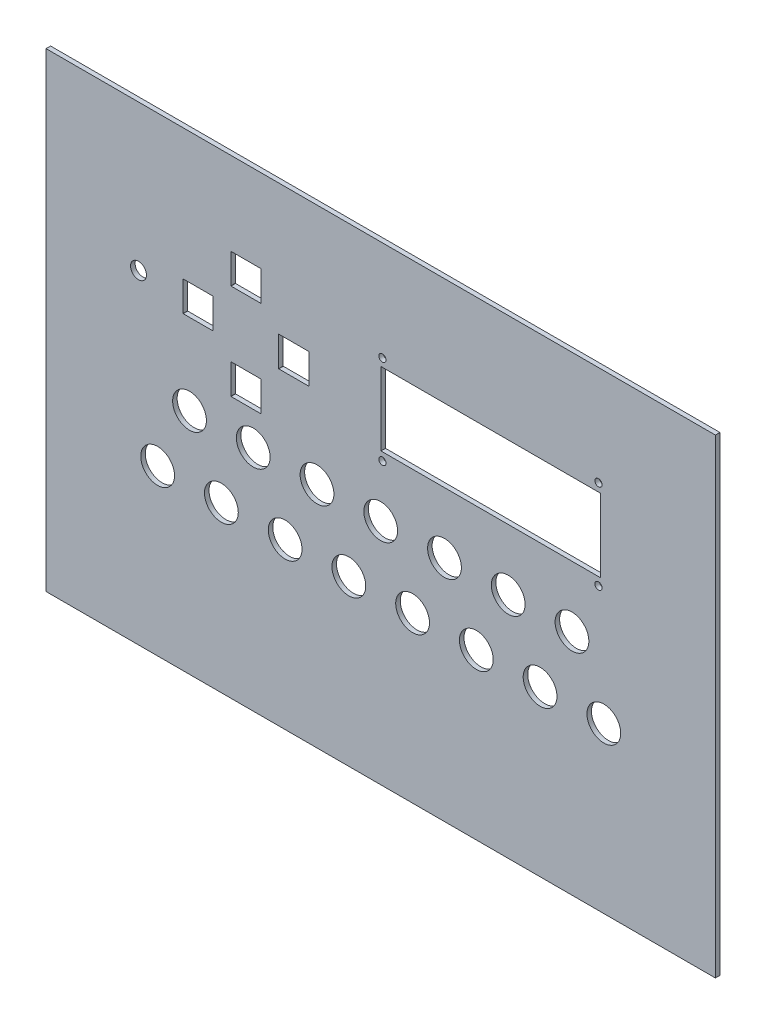
SolidWorks part; units mm, degrees
ref_plane "Front Plane" through (0, 0, 0) normal (0, 0, 1) x (1, 0, 0)
ref_plane "Top Plane" through (0, 0, 0) normal (0, 1, 0) x (1, 0, 0)
ref_plane "Right Plane" through (0, 0, 0) normal (1, 0, 0) x (0, 0, -1)
sketch "Model" plane through (0, 0, 0) normal (0, 0, 1) x (1, 0, 0)
  line L21 (196.2082, 34.8915) -> (-36.2018, 34.8915)
  line L22 (196.2082, 34.8915) -> (196.2082, 198.1627)
  line L23 (196.2082, 198.1627) -> (-36.2018, 198.1627)
  line L24 (-36.2018, 34.8915) -> (-36.2018, 198.1627)
  point P16 (80.0032, 34.8915)
  line B0 (28.0165, 169.3095) -> (38.375, 169.3095)
  line B1 (38.4192, 169.2652) -> (38.4192, 158.9068)
  line B2 (38.375, 158.8625) -> (28.0165, 158.8625)
  line B3 (27.9722, 158.9068) -> (27.9722, 169.2652)
  line B4 (28.0165, 136.1093) -> (38.375, 136.1093)
  line B5 (38.4192, 136.065) -> (38.4192, 125.7065)
  line B6 (38.375, 125.6623) -> (28.0165, 125.6623)
  line B7 (27.9722, 125.7065) -> (27.9722, 136.065)
  line B8 (44.6166, 152.7094) -> (54.9751, 152.7094)
  line B9 (55.0194, 152.6651) -> (55.0194, 142.3066)
  line B10 (54.9751, 142.2624) -> (44.6166, 142.2624)
  line B11 (44.5724, 142.3066) -> (44.5724, 152.6651)
  line B12 (21.8191, 152.6651) -> (21.8191, 142.3066)
  line B13 (21.7749, 142.2624) -> (11.4164, 142.2624)
  line B14 (11.3721, 142.3066) -> (11.3721, 152.6651)
  line B15 (11.4164, 152.7094) -> (21.7749, 152.7094)
  line B16 (146.0717, 154.0706) -> (146.0717, 141.9636)
  line B17 (146.0274, 141.9193) -> (90.3395, 141.9193)
  line B18 (90.2953, 141.9636) -> (90.2953, 154.0706)
  line B19 (90.3395, 154.1149) -> (146.0274, 154.1149)
  circle B20 centre (-4.1041, 147.4859) radius 2.7667
  circle B21 centre (68.9365, 92.0415) radius 5.8654
  circle B22 centre (2.536, 92.0415) radius 5.8654
  circle B23 centre (24.6695, 92.0415) radius 5.8654
  circle B24 centre (46.803, 92.0415) radius 5.8654
  circle B25 centre (91.07, 92.0415) radius 5.8654
  circle B26 centre (113.2034, 92.0415) radius 5.8654
  circle B27 centre (135.3369, 92.0415) radius 5.8654
  circle B28 centre (157.4704, 92.0415) radius 5.8654
  circle B29 centre (146.4037, 114.175) radius 5.8654
  circle B30 centre (124.2702, 114.175) radius 5.8654
  circle B31 centre (102.1367, 114.175) radius 5.8654
  circle B32 centre (80.0032, 114.175) radius 5.8654
  circle B33 centre (57.8697, 114.175) radius 5.8654
  circle B34 centre (35.7362, 114.175) radius 5.8654
  circle B35 centre (13.6027, 114.175) radius 5.8654
  arc B36 (38.4192, 169.2652) -> (38.375, 169.3095) centre (38.375, 169.2652) ccw
  arc B37 (38.375, 158.8625) -> (38.4192, 158.9068) centre (38.375, 158.9068) ccw
  arc B38 (27.9722, 158.9068) -> (28.0165, 158.8625) centre (28.0165, 158.9068) ccw
  arc B39 (28.0165, 169.3095) -> (27.9722, 169.2652) centre (28.0165, 169.2652) ccw
  arc B40 (38.4192, 136.065) -> (38.375, 136.1093) centre (38.375, 136.065) ccw
  arc B41 (38.375, 125.6623) -> (38.4192, 125.7065) centre (38.375, 125.7065) ccw
  arc B42 (27.9722, 125.7065) -> (28.0165, 125.6623) centre (28.0165, 125.7065) ccw
  arc B43 (28.0165, 136.1093) -> (27.9722, 136.065) centre (28.0165, 136.065) ccw
  arc B44 (55.0194, 152.6651) -> (54.9751, 152.7094) centre (54.9751, 152.6651) ccw
  arc B45 (54.9751, 142.2624) -> (55.0194, 142.3066) centre (54.9751, 142.3066) ccw
  arc B46 (44.5724, 142.3066) -> (44.6166, 142.2624) centre (44.6166, 142.3066) ccw
  arc B47 (44.6166, 152.7094) -> (44.5724, 152.6651) centre (44.6166, 152.6651) ccw
  arc B48 (21.7749, 142.2624) -> (21.8191, 142.3066) centre (21.7749, 142.3066) ccw
  arc B49 (11.3721, 142.3066) -> (11.4164, 142.2624) centre (11.4164, 142.3066) ccw
  arc B50 (11.4164, 152.7094) -> (11.3721, 152.6651) centre (11.4164, 152.6651) ccw
  arc B51 (21.8191, 152.6651) -> (21.7749, 152.7094) centre (21.7749, 152.6651) ccw
  arc B52 (146.0274, 141.9193) -> (146.0717, 141.9636) centre (146.0274, 141.9636) ccw
  arc B53 (90.2953, 141.9636) -> (90.3395, 141.9193) centre (90.3395, 141.9636) ccw
  arc B54 (90.3395, 154.1149) -> (90.2953, 154.0706) centre (90.3395, 154.0706) ccw
  arc B55 (146.0717, 154.0706) -> (146.0274, 154.1149) centre (146.0274, 154.0706) ccw
  dimension "D1" = 232.41
  dimension "D2" = 163.2712
  dimension "D3" = 0
  dimension "D4" = 57.15
sketch_block_instance "Block2-1"
sketch_block "Block2"
extrude "Boss-Extrude2" add sketch "Model" along normal blind 1.5748
sketch "Sketch10" plane through (0, 0, 1.5748) normal (0, 0, 1) x (1, 0, 0)
  line L0 (90.2953, 154.0706) -> (90.2953, 141.9636) construction
  line L1 (80.0835, 160.7171) -> (156.2835, 160.7171)
  line L2 (80.0835, 160.7171) -> (80.0835, 135.3171)
  line L3 (80.0835, 135.3171) -> (156.2835, 135.3171)
  line L4 (156.2835, 160.7171) -> (156.2835, 135.3171)
  line L5 (90.3395, 141.9193) -> (146.0274, 141.9193) construction
  point P6 (90.2953, 148.0171)
  point P7 (80.0835, 148.0171)
  point P8 (118.1835, 141.9193)
  point P11 (118.1835, 135.3171)
  dimension "D1" = 0
  dimension "D2" = 0
  dimension "D3" = 76.2
  dimension "D4" = 25.4
extrude "Cut-Extrude13" cut sketch "Sketch10" against normal blind 1.5748
sketch "Sketch11" plane through (0, 0, 0) normal (0, 0, -1) x (-1, 0, 0)
  circle A0 centre (-155.6104, 163.5238) radius 1.2446
  circle A1 centre (-155.6104, 132.5104) radius 1.2446
  circle A2 centre (-80.5788, 132.5104) radius 1.2446
  circle A3 centre (-80.5788, 163.5238) radius 1.2446
extrude "Cut-Extrude14" cut sketch "Sketch11" against normal through all
